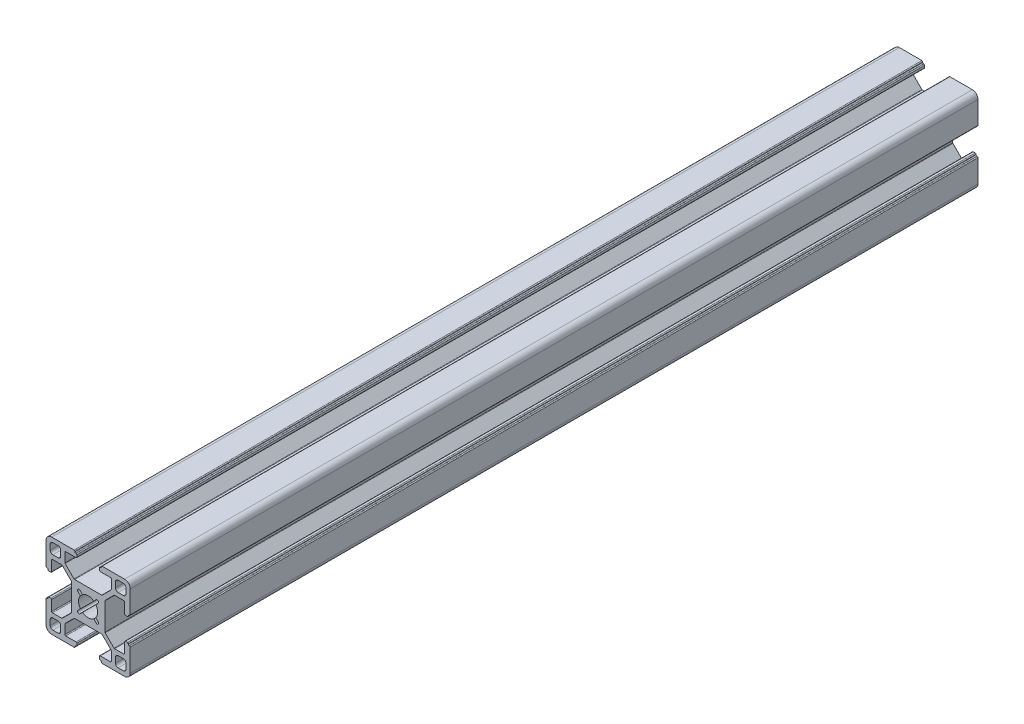
SolidWorks part; units mm, degrees
ref_plane "Piano frontale" through (0, 0, 0) normal (0, 0, 1) x (1, 0, 0)
ref_plane "Piano superiore" through (0, 0, 0) normal (0, 1, 0) x (1, 0, 0)
ref_plane "Piano destro" through (0, 0, 0) normal (1, 0, 0) x (0, 0, -1)
ref_plane "Piano1" through (0, 0, 25) normal (0, 0, 1) x (1, 0, 0)
sketch "Schizzo1" plane through (0, 0, 25) normal (0, 0, 1) x (1, 0, 0)
  line L0 (-12.5625, -9.75) -> (-10.6875, -9.75)
  line L1 (-9.75, -10.6875) -> (-9.75, -12.5625)
  line L2 (-10.6875, -13.5) -> (-12.5625, -13.5)
  line L3 (-13.5, -12.5625) -> (-13.5, -10.6875)
  line L4 (12.5625, 9.75) -> (10.6875, 9.75)
  line L5 (9.75, 10.6875) -> (9.75, 12.5625)
  line L6 (10.6875, 13.5) -> (12.5625, 13.5)
  line L7 (13.5, 12.5625) -> (13.5, 10.6875)
  line L8 (-4.7, -14.7) -> (-4.7, -14.6)
  line L9 (-4.4, -14.3) -> (-4.3, -14.3)
  line L10 (-4, -14) -> (-4, -13.3)
  line L11 (-4.3, -13) -> (-7.95, -13)
  line L12 (-8.25, -12.7) -> (-8.25, -9.4349)
  line L13 (-8.1621, -9.2228) -> (-5.0272, -6.0879)
  line L14 (-4.8151, -6) -> (4.8151, -6)
  line L15 (5.0272, -6.0879) -> (8.1621, -9.2228)
  line L16 (8.25, -9.4349) -> (8.25, -12.7)
  line L17 (7.95, -13) -> (4.3, -13)
  line L18 (4, -13.3) -> (4, -14)
  line L19 (4.3, -14.3) -> (4.4, -14.3)
  line L20 (4.7, -14.6) -> (4.7, -14.7)
  line L21 (5, -15) -> (13, -15)
  line L22 (15, -13) -> (15, -5)
  line L23 (14.7, -4.7) -> (14.6, -4.7)
  line L24 (14.3, -4.4) -> (14.3, -4.3)
  line L25 (14, -4) -> (13.3, -4)
  line L26 (13, -4.3) -> (13, -7.95)
  line L27 (12.7, -8.25) -> (9.4349, -8.25)
  line L28 (9.2228, -8.1621) -> (6.0879, -5.0272)
  line L29 (6, -4.8151) -> (6, 4.8151)
  line L30 (6.0879, 5.0272) -> (9.2228, 8.1621)
  line L31 (9.4349, 8.25) -> (12.7, 8.25)
  line L32 (13, 7.95) -> (13, 4.3)
  line L33 (13.3, 4) -> (14, 4)
  line L34 (14.3, 4.3) -> (14.3, 4.4)
  line L35 (14.6, 4.7) -> (14.7, 4.7)
  line L36 (15, 5) -> (15, 13)
  line L37 (13, 15) -> (5, 15)
  line L38 (4.7, 14.7) -> (4.7, 14.6)
  line L39 (4.4, 14.3) -> (4.3, 14.3)
  line L40 (4, 14) -> (4, 13.3)
  line L41 (4.3, 13) -> (7.95, 13)
  line L42 (8.25, 12.7) -> (8.25, 9.4349)
  line L43 (8.1621, 9.2228) -> (5.0272, 6.0879)
  line L44 (4.8151, 6) -> (-4.8151, 6)
  line L45 (-5.0272, 6.0879) -> (-8.1621, 9.2228)
  line L46 (-8.25, 9.4349) -> (-8.25, 12.7)
  line L47 (-7.95, 13) -> (-4.3, 13)
  line L48 (-4, 13.3) -> (-4, 14)
  line L49 (-4.3, 14.3) -> (-4.4, 14.3)
  line L50 (-4.7, 14.6) -> (-4.7, 14.7)
  line L51 (-5, 15) -> (-13, 15)
  line L52 (-15, 13) -> (-15, 5)
  line L53 (-14.7, 4.7) -> (-14.6, 4.7)
  line L54 (-14.3, 4.4) -> (-14.3, 4.3)
  line L55 (-14, 4) -> (-13.3, 4)
  line L56 (-13, 4.3) -> (-13, 7.95)
  line L57 (-12.7, 8.25) -> (-9.4349, 8.25)
  line L58 (-9.2228, 8.1621) -> (-6.0879, 5.0272)
  line L59 (-6, 4.8151) -> (-6, -4.8151)
  line L60 (-6.0879, -5.0272) -> (-9.2228, -8.1621)
  line L61 (-9.4349, -8.25) -> (-12.7, -8.25)
  line L62 (-13, -7.95) -> (-13, -4.3)
  line L63 (-13.3, -4) -> (-14, -4)
  line L64 (-14.3, -4.3) -> (-14.3, -4.4)
  line L65 (-14.6, -4.7) -> (-14.7, -4.7)
  line L66 (-15, -5) -> (-15, -13)
  line L67 (-13, -15) -> (-5, -15)
  line L68 (2.0101, 2.7422) -> (2.8679, 3.6)
  line L69 (3.6, 2.8679) -> (2.7422, 2.0101)
  line L70 (2.7422, -2.0101) -> (3.6, -2.8679)
  line L71 (2.8679, -3.6) -> (2.0101, -2.7422)
  line L72 (-2.0101, -2.7422) -> (-2.8679, -3.6)
  line L73 (-3.6, -2.8679) -> (-2.7422, -2.0101)
  line L74 (-2.7422, 2.0101) -> (-3.6, 2.8679)
  line L75 (-2.8679, 3.6) -> (-2.0101, 2.7422)
  line L76 (-9.75, 12.5625) -> (-9.75, 10.6875)
  line L77 (-10.6875, 9.75) -> (-12.5625, 9.75)
  line L78 (-13.5, 10.6875) -> (-13.5, 12.5625)
  line L79 (-12.5625, 13.5) -> (-10.6875, 13.5)
  line L80 (9.75, -12.5625) -> (9.75, -10.6875)
  line L81 (10.6875, -9.75) -> (12.5625, -9.75)
  line L82 (13.5, -10.6875) -> (13.5, -12.5625)
  line L83 (12.5625, -13.5) -> (10.6875, -13.5)
  arc A0 (-10.6875, -9.75) -> (-9.75, -10.6875) centre (-10.6875, -10.6875) cw
  arc A1 (-9.75, -12.5625) -> (-10.6875, -13.5) centre (-10.6875, -12.5625) cw
  arc A2 (-12.5625, -13.5) -> (-13.5, -12.5625) centre (-12.5625, -12.5625) cw
  arc A3 (-13.5, -10.6875) -> (-12.5625, -9.75) centre (-12.5625, -10.6875) cw
  arc A4 (10.6875, 9.75) -> (9.75, 10.6875) centre (10.6875, 10.6875) cw
  arc A5 (9.75, 12.5625) -> (10.6875, 13.5) centre (10.6875, 12.5625) cw
  arc A6 (12.5625, 13.5) -> (13.5, 12.5625) centre (12.5625, 12.5625) cw
  arc A7 (13.5, 10.6875) -> (12.5625, 9.75) centre (12.5625, 10.6875) cw
  arc A8 (-5, -15) -> (-4.7, -14.7) centre (-5, -14.7) ccw
  arc A9 (-4.7, -14.6) -> (-4.4, -14.3) centre (-4.4, -14.6) cw
  arc A10 (-4.3, -14.3) -> (-4, -14) centre (-4.3, -14) ccw
  arc A11 (-4, -13.3) -> (-4.3, -13) centre (-4.3, -13.3) ccw
  arc A12 (-7.95, -13) -> (-8.25, -12.7) centre (-7.95, -12.7) cw
  arc A13 (-8.25, -9.4349) -> (-8.1621, -9.2228) centre (-7.95, -9.4349) cw
  arc A14 (-5.0272, -6.0879) -> (-4.8151, -6) centre (-4.8151, -6.3) cw
  arc A15 (4.8151, -6) -> (5.0272, -6.0879) centre (4.8151, -6.3) cw
  arc A16 (8.1621, -9.2228) -> (8.25, -9.4349) centre (7.95, -9.4349) cw
  arc A17 (8.25, -12.7) -> (7.95, -13) centre (7.95, -12.7) cw
  arc A18 (4.3, -13) -> (4, -13.3) centre (4.3, -13.3) ccw
  arc A19 (4, -14) -> (4.3, -14.3) centre (4.3, -14) ccw
  arc A20 (4.4, -14.3) -> (4.7, -14.6) centre (4.4, -14.6) cw
  arc A21 (4.7, -14.7) -> (5, -15) centre (5, -14.7) ccw
  arc A22 (13, -15) -> (15, -13) centre (13, -13) ccw
  arc A23 (15, -5) -> (14.7, -4.7) centre (14.7, -5) ccw
  arc A24 (14.6, -4.7) -> (14.3, -4.4) centre (14.6, -4.4) cw
  arc A25 (14.3, -4.3) -> (14, -4) centre (14, -4.3) ccw
  arc A26 (13.3, -4) -> (13, -4.3) centre (13.3, -4.3) ccw
  arc A27 (13, -7.95) -> (12.7, -8.25) centre (12.7, -7.95) cw
  arc A28 (9.4349, -8.25) -> (9.2228, -8.1621) centre (9.4349, -7.95) cw
  arc A29 (6.0879, -5.0272) -> (6, -4.8151) centre (6.3, -4.8151) cw
  arc A30 (6, 4.8151) -> (6.0879, 5.0272) centre (6.3, 4.8151) cw
  arc A31 (9.2228, 8.1621) -> (9.4349, 8.25) centre (9.4349, 7.95) cw
  arc A32 (12.7, 8.25) -> (13, 7.95) centre (12.7, 7.95) cw
  arc A33 (13, 4.3) -> (13.3, 4) centre (13.3, 4.3) ccw
  arc A34 (14, 4) -> (14.3, 4.3) centre (14, 4.3) ccw
  arc A35 (14.3, 4.4) -> (14.6, 4.7) centre (14.6, 4.4) cw
  arc A36 (14.7, 4.7) -> (15, 5) centre (14.7, 5) ccw
  arc A37 (15, 13) -> (13, 15) centre (13, 13) ccw
  arc A38 (5, 15) -> (4.7, 14.7) centre (5, 14.7) ccw
  arc A39 (4.7, 14.6) -> (4.4, 14.3) centre (4.4, 14.6) cw
  arc A40 (4.3, 14.3) -> (4, 14) centre (4.3, 14) ccw
  arc A41 (4, 13.3) -> (4.3, 13) centre (4.3, 13.3) ccw
  arc A42 (7.95, 13) -> (8.25, 12.7) centre (7.95, 12.7) cw
  arc A43 (8.25, 9.4349) -> (8.1621, 9.2228) centre (7.95, 9.4349) cw
  arc A44 (5.0272, 6.0879) -> (4.8151, 6) centre (4.8151, 6.3) cw
  arc A45 (-4.8151, 6) -> (-5.0272, 6.0879) centre (-4.8151, 6.3) cw
  arc A46 (-8.1621, 9.2228) -> (-8.25, 9.4349) centre (-7.95, 9.4349) cw
  arc A47 (-8.25, 12.7) -> (-7.95, 13) centre (-7.95, 12.7) cw
  arc A48 (-4.3, 13) -> (-4, 13.3) centre (-4.3, 13.3) ccw
  arc A49 (-4, 14) -> (-4.3, 14.3) centre (-4.3, 14) ccw
  arc A50 (-4.4, 14.3) -> (-4.7, 14.6) centre (-4.4, 14.6) cw
  arc A51 (-4.7, 14.7) -> (-5, 15) centre (-5, 14.7) ccw
  arc A52 (-13, 15) -> (-15, 13) centre (-13, 13) ccw
  arc A53 (-15, 5) -> (-14.7, 4.7) centre (-14.7, 5) ccw
  arc A54 (-14.6, 4.7) -> (-14.3, 4.4) centre (-14.6, 4.4) cw
  arc A55 (-14.3, 4.3) -> (-14, 4) centre (-14, 4.3) ccw
  arc A56 (-13.3, 4) -> (-13, 4.3) centre (-13.3, 4.3) ccw
  arc A57 (-13, 7.95) -> (-12.7, 8.25) centre (-12.7, 7.95) cw
  arc A58 (-9.4349, 8.25) -> (-9.2228, 8.1621) centre (-9.4349, 7.95) cw
  arc A59 (-6.0879, 5.0272) -> (-6, 4.8151) centre (-6.3, 4.8151) cw
  arc A60 (-6, -4.8151) -> (-6.0879, -5.0272) centre (-6.3, -4.8151) cw
  arc A61 (-9.2228, -8.1621) -> (-9.4349, -8.25) centre (-9.4349, -7.95) cw
  arc A62 (-12.7, -8.25) -> (-13, -7.95) centre (-12.7, -7.95) cw
  arc A63 (-13, -4.3) -> (-13.3, -4) centre (-13.3, -4.3) ccw
  arc A64 (-14, -4) -> (-14.3, -4.3) centre (-14, -4.3) ccw
  arc A65 (-14.3, -4.4) -> (-14.6, -4.7) centre (-14.6, -4.4) cw
  arc A66 (-14.7, -4.7) -> (-15, -5) centre (-14.7, -5) ccw
  arc A67 (-15, -13) -> (-13, -15) centre (-13, -13) ccw
  arc A68 (2.8679, 3.6) -> (3.6, 2.8679) centre (3.234, 3.234) cw
  arc A69 (2.7422, 2.0101) -> (2.7422, -2.0101) centre (0, 0) cw
  arc A70 (3.6, -2.8679) -> (2.8679, -3.6) centre (3.234, -3.234) cw
  arc A71 (2.0101, -2.7422) -> (-2.0101, -2.7422) centre (0, 0) cw
  arc A72 (-2.8679, -3.6) -> (-3.6, -2.8679) centre (-3.234, -3.234) cw
  arc A73 (-2.7422, -2.0101) -> (-2.7422, 2.0101) centre (0, 0) cw
  arc A74 (-3.6, 2.8679) -> (-2.8679, 3.6) centre (-3.234, 3.234) cw
  arc A75 (-2.0101, 2.7422) -> (2.0101, 2.7422) centre (0, 0) cw
  arc A76 (-9.75, 10.6875) -> (-10.6875, 9.75) centre (-10.6875, 10.6875) cw
  arc A77 (-12.5625, 9.75) -> (-13.5, 10.6875) centre (-12.5625, 10.6875) cw
  arc A78 (-13.5, 12.5625) -> (-12.5625, 13.5) centre (-12.5625, 12.5625) cw
  arc A79 (-10.6875, 13.5) -> (-9.75, 12.5625) centre (-10.6875, 12.5625) cw
  arc A80 (9.75, -10.6875) -> (10.6875, -9.75) centre (10.6875, -10.6875) cw
  arc A81 (12.5625, -9.75) -> (13.5, -10.6875) centre (12.5625, -10.6875) cw
  arc A82 (13.5, -12.5625) -> (12.5625, -13.5) centre (12.5625, -12.5625) cw
  arc A83 (10.6875, -13.5) -> (9.75, -12.5625) centre (10.6875, -12.5625) cw
extrude "Estrusione-Estrusione1" add sketch "Schizzo1" against normal blind 302
